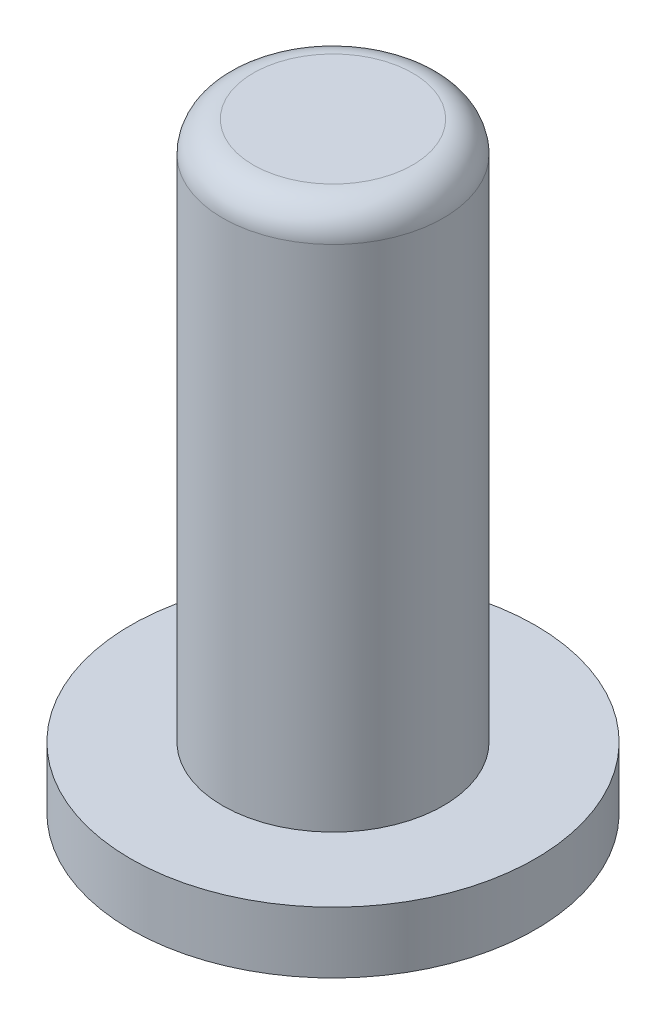
SolidWorks part; units mm, degrees
ref_plane "前视基准面" through (0, 0, 0) normal (0, 0, 1) x (1, 0, 0)
ref_plane "上视基准面" through (0, 0, 0) normal (0, 1, 0) x (1, 0, 0)
ref_plane "右视基准面" through (0, 0, 0) normal (1, 0, 0) x (0, 0, -1)
sketch "草图1" plane through (0, 0, 0) normal (0, 1, 0) x (1, 0, 0)
  circle A0 centre (0, 0) radius 3.3
  dimension "D1" = 6.6
extrude "凸台-拉伸1" add sketch "草图1" along normal blind 1
sketch "草图2" plane through (0, 1, 0) normal (0, 1, 0) x (1, 0, 0)
  circle A0 centre (0, 0) radius 1.8
  dimension "D1" = 3.6
extrude "凸台-拉伸2" add sketch "草图2" along normal blind 8.8
fillet "圆角1" radius 0.5 1 edges at (0, 9.8, 1.8)
